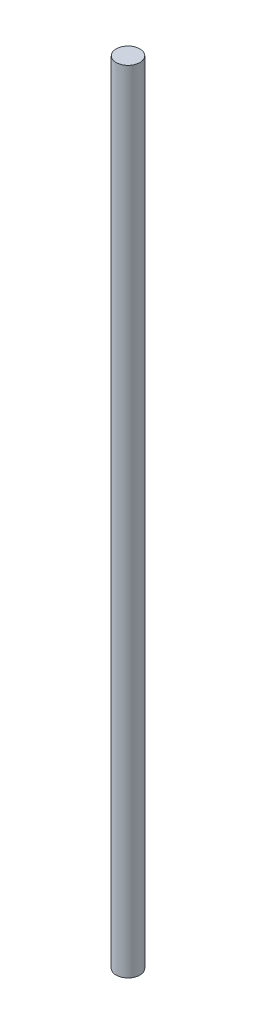
SolidWorks part; units mm, degrees
material "6061 Alloy"
ref_plane "Front Plane" through (0, 0, 0) normal (0, 0, 1) x (1, 0, 0)
ref_plane "Top Plane" through (0, 0, 0) normal (0, 1, 0) x (1, 0, 0)
ref_plane "Right Plane" through (0, 0, 0) normal (1, 0, 0) x (0, 0, -1)
sketch "Sketch1" plane through (0, 0, 0) normal (0, 1, 0) x (1, 0, 0)
  circle A0 centre (0, 0) radius 3
  dimension "Diam" = 6
extrude "Boss-Extrude1" add sketch "Sketch1" along normal mid plane 200
